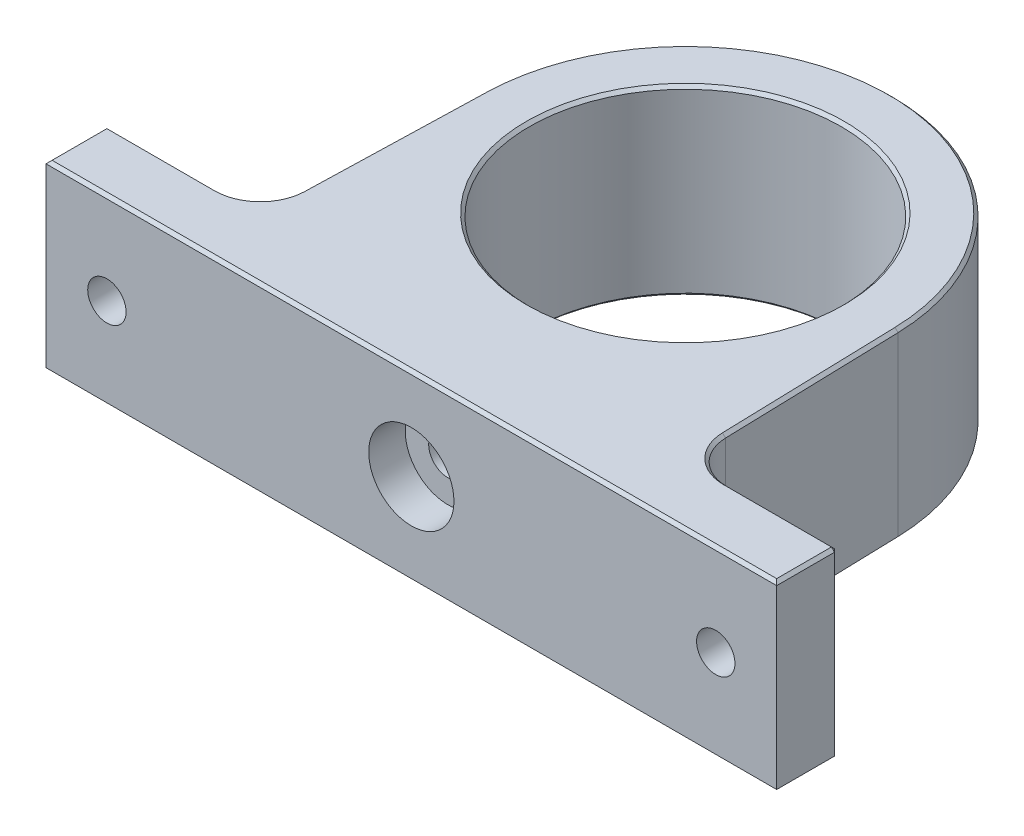
SolidWorks part; units mm, degrees
ref_plane "Front Plane" through (0, 0, 0) normal (0, 0, 1) x (1, 0, 0)
ref_plane "Top Plane" through (0, 0, 0) normal (0, 1, 0) x (1, 0, 0)
ref_plane "Right Plane" through (0, 0, 0) normal (1, 0, 0) x (0, 0, -1)
sketch "Sketch1" plane through (0, 0, 0) normal (0, 1, 0) x (1, 0, 0)
  line L0 (-33.9865, 0.9579) -> (-35, -35)
  line L1 (-35, -35) -> (35, -35) construction
  line L2 (35, -35) -> (33.9865, 0.9579)
  line L3 (-35, -35) -> (-60, -35)
  line L4 (-60, -35) -> (-60, -45)
  line L5 (-60, -45) -> (60, -45)
  line L6 (60, -45) -> (60, -35)
  line L7 (60, -35) -> (35, -35)
  circle A0 centre (0, 0) radius 25.6
  arc A1 (33.9865, 0.9579) -> (-33.9865, 0.9579) centre (0, 0) ccw
  dimension "D1" = 51.2
  dimension "D2" = 68
  dimension "D3" = 70
  dimension "D4" = 35
  dimension "D5" = 10
  dimension "D6" = 120
  dimension "D7" = 25
extrude "Boss-Extrude1" add sketch "Sketch1" along normal mid plane 30
sketch "Sketch2" plane through (0, 0, 45) normal (0, 0, 1) x (1, 0, 0)
  circle A0 centre (0, 0) radius 3.15
  dimension "D1" = 6.3
extrude "Cut-Extrude1" cut sketch "Sketch2" against normal blind 30
sketch "Sketch3" plane through (0, 0, 45) normal (0, 0, 1) x (1, 0, 0)
  circle A0 centre (0, 0) radius 7
  dimension "D1" = 14
extrude "Cut-Extrude2" cut sketch "Sketch3" against normal blind 6
sketch "Sketch4" plane through (0, 0, 35) normal (0, 0, -1) x (-1, 0, 0)
  line L0 (0, 0) -> (-50, 0) construction
  line L1 (0, 0) -> (50, 0) construction
  circle A0 centre (-50, 0) radius 3.15
  circle A1 centre (50, 0) radius 3.15
  dimension "D1" = 100
  dimension "D2" = 6.3
extrude "Cut-Extrude3" cut sketch "Sketch4" against normal through all
fillet "Fillet1" radius 7 2 edges at (-35, 0, 35) (35, 0, 35)
chamfer "Chamfer1" distance 0.5 angle 45 26 edges at (0, 15, 25.6) (0, -15, 25.6) (-53.15, 0, 35) (46.85, 0, 35) (60, 15, 40) (0, 15, 45) (-60, 15, 40) (-36.926, 15, 33.019) (-34.3974, 15, 13.6196) (0, 15, -34) (34.3974, 15, 13.6196) (36.926, 15, 33.019) (36.926, -15, 33.019) (34.3974, -15, 13.6196) (50.9027, 15, 35) (60, 0, 35) (50.9027, -15, 35) (60, -15, 40) (0, -15, 45) (-60, -15, 40) (-50.9027, 15, 35) (-60, 0, 35) (-50.9027, -15, 35) (-36.926, -15, 33.019) (-34.3974, -15, 13.6196) (0, -15, -34)
sketch "Sketch5" plane through (0, 0, 0) normal (0, 0, 1) x (1, 0, 0)
  line L1 (2.9445, 5.1) -> (-2.9445, 5.1)
  line L2 (-2.9445, 5.1) -> (-5.889, 0)
  line L3 (-5.889, 0) -> (-2.9445, -5.1)
  line L4 (-2.9445, -5.1) -> (2.9445, -5.1)
  line L5 (2.9445, -5.1) -> (5.889, 0)
  line L6 (5.889, 0) -> (2.9445, 5.1)
  circle A0 centre (0, 0) radius 5.1 construction
  dimension "D1" = 10.2
extrude "Cut-Extrude4" cut sketch "Sketch5" along normal blind 33
